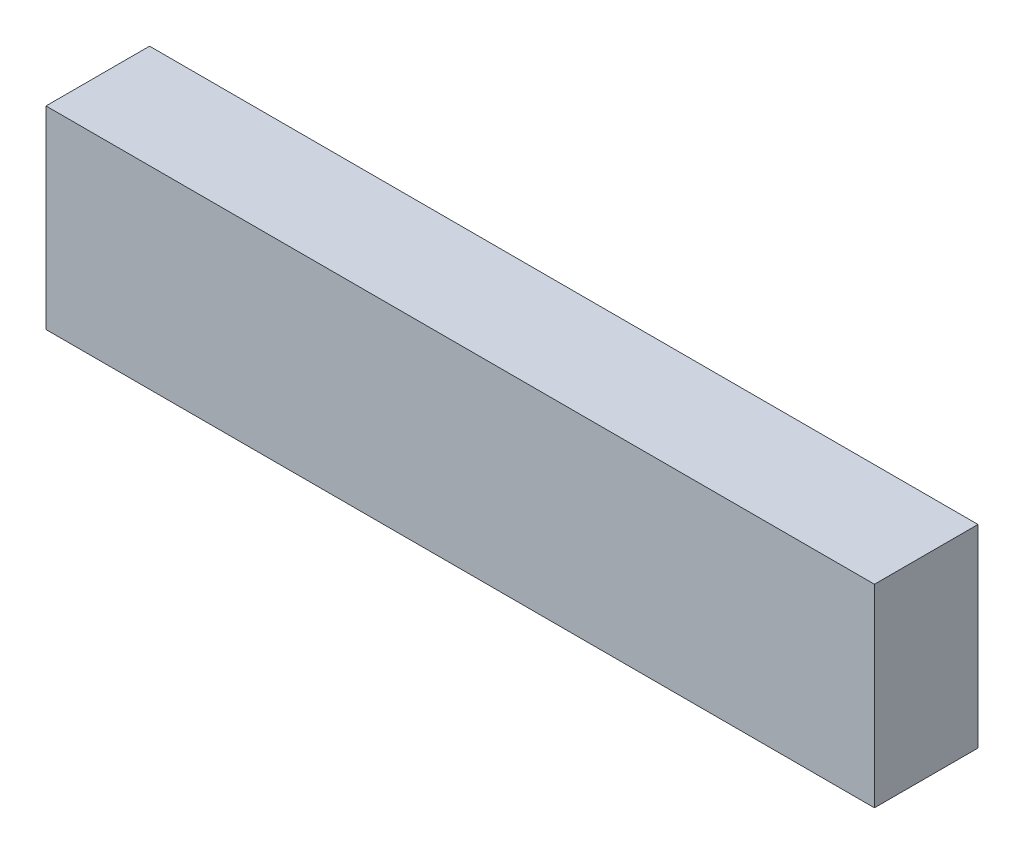
SolidWorks part; units mm, degrees
ref_plane "Front Plane" through (0, 0, 0) normal (0, 0, 1) x (1, 0, 0)
ref_plane "Top Plane" through (0, 0, 0) normal (0, 1, 0) x (1, 0, 0)
ref_plane "Right Plane" through (0, 0, 0) normal (1, 0, 0) x (0, 0, -1)
sketch "Sketch1" plane through (0, 0, 0) normal (0, 1, 0) x (1, 0, 0)
  line L1 (0, 0) -> (50.8, 0)
  line L2 (0, 0) -> (0, -6.35)
  line L3 (0, -6.35) -> (50.8, -6.35)
  line L4 (50.8, 0) -> (50.8, -6.35)
  dimension "D1" = 50.8
  dimension "D2" = 6.35
extrude "Boss-Extrude1" add sketch "Sketch1" along normal blind 11.875
